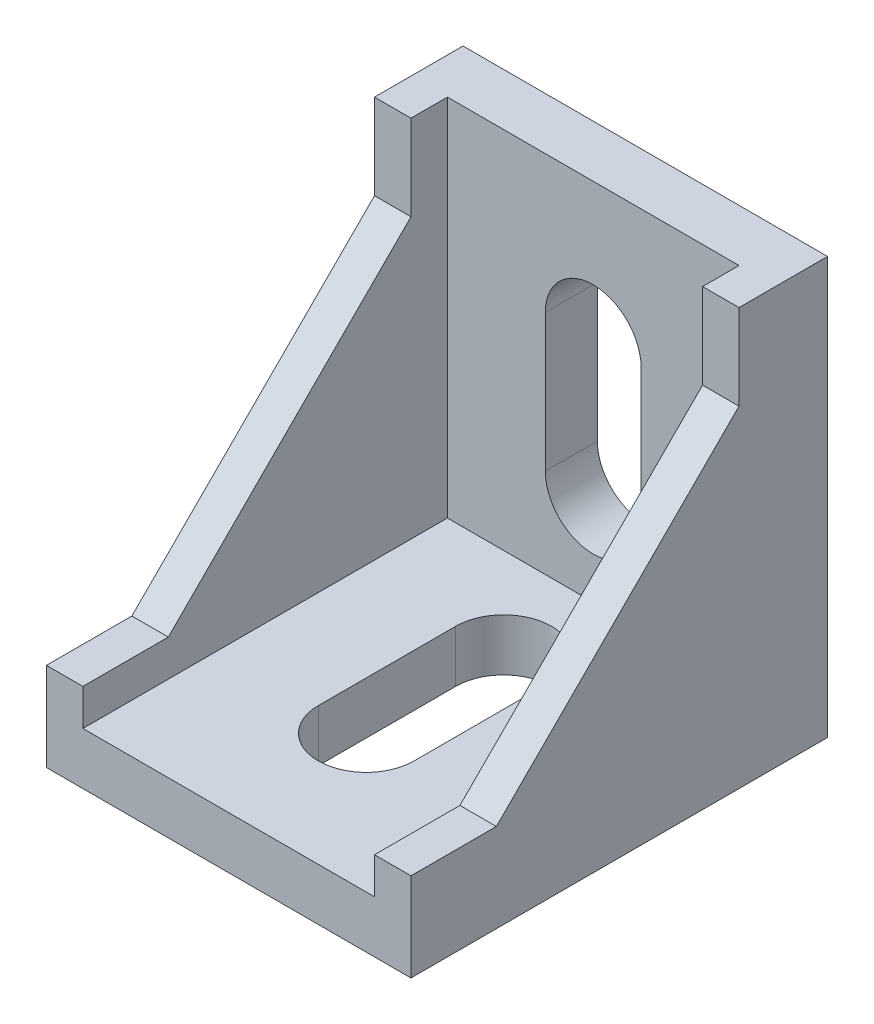
SolidWorks part; units mm, degrees
ref_plane "前视基准面" through (0, 0, 0) normal (0, 0, 1) x (1, 0, 0)
ref_plane "上视基准面" through (0, 0, 0) normal (0, 1, 0) x (1, 0, 0)
ref_plane "右视基准面" through (0, 0, 0) normal (1, 0, 0) x (0, 0, -1)
sketch "草图3" plane through (0, 0, 0) normal (0, 0, 1) x (1, 0, 0)
  line L0 (0, 26.8) -> (0, 13.6) construction
  line L1 (-17.5, 40) -> (17.5, 40)
  line L2 (-17.5, 40) -> (-17.5, 0)
  line L3 (-17.5, 0) -> (17.5, 0)
  line L4 (17.5, 40) -> (17.5, 0)
  line L5 (4.6, 26.8) -> (4.6, 13.6)
  line L6 (-4.6, 26.8) -> (-4.6, 13.6)
  arc A0 (4.6, 26.8) -> (-4.6, 26.8) centre (0, 26.8) ccw
  arc A1 (-4.6, 13.6) -> (4.6, 13.6) centre (0, 13.6) ccw
  point P4 (0, 0)
  point P8 (0, 20.2)
  dimension "D3" = 22.4
  dimension "D4" = 8.6
  dimension "D1" = 35
  dimension "D2" = 40
  dimension "D5" = 9.2
extrude "凸台-拉伸1" add sketch "草图3" along normal blind 5
sketch "草图4" plane through (-17.5, 0, 0) normal (-1, 0, 0) x (0, 0, 1)
  line L0 (5, 40) -> (8.5, 40)
  line L1 (8.5, 40) -> (8.5, 31.8)
  line L2 (8.5, 31.8) -> (31.8, 8.5)
  line L3 (31.8, 8.5) -> (40, 8.5)
  line L4 (40, 8.5) -> (40, 0)
  line L5 (40, 0) -> (5, 0)
  line L6 (5, 0) -> (5, 40)
  line L7 (0, 40) -> (0, 0) construction
  dimension "D1" = 8.5
  dimension "D2" = 8.5
  dimension "D3" = 40
  dimension "D4" = 8.2
extrude "凸台-拉伸2" add sketch "草图4" against normal blind 3.5
mirror "镜向1" about plane through (0, 0, 0) normal (1, 0, 0) of "凸台-拉伸2"
sketch "草图5" plane through (0, 0, 0) normal (0, -1, 0) x (1, 0, 0)
  line L0 (0, 26.8) -> (0, 13.6) construction
  line L1 (-17.5, 0) -> (17.5, 0)
  line L2 (-17.5, 0) -> (-17.5, 40)
  line L3 (-17.5, 40) -> (17.5, 40)
  line L4 (17.5, 0) -> (17.5, 40)
  line L5 (4.6, 26.8) -> (4.6, 13.6)
  line L6 (-4.6, 26.8) -> (-4.6, 13.6)
  arc A0 (4.6, 26.8) -> (-4.6, 26.8) centre (0, 26.8) ccw
  arc A1 (-4.6, 13.6) -> (4.6, 13.6) centre (0, 13.6) ccw
  point P9 (0, 20.2)
  dimension "D2" = 22.4
  dimension "D3" = 8.6
  dimension "D1" = 9.2
extrude "凸台-拉伸3" add sketch "草图5" against normal blind 5
sketch "草图6" plane through (0, 0, 0) normal (1, 0, 0) x (0, 0, -1)
  line L0 (-40, 0) -> (0, 0) construction
  line L1 (-36, 0) -> (-34, 0)
  line L2 (-36, 0) -> (-36, -1.5)
  line L3 (-36, -1.5) -> (-34, -1.5)
  line L4 (-34, 0) -> (-34, -1.5)
  line L5 (-40, 0) -> (-40, 8.5) construction
  line L6 (-20, 0) -> (-20, -10.5773) construction
  line L7 (-6, 0) -> (-6, -1.5)
  line L8 (-4, -1.5) -> (-6, -1.5)
  line L9 (-4, 0) -> (-4, -1.5)
  line L10 (-4, 0) -> (-6, 0)
  line L12 (0, 4) -> (0, 6)
  line L13 (0, 4) -> (1.5, 4)
  line L14 (1.5, 4) -> (1.5, 6)
  line L15 (0, 6) -> (1.5, 6)
  line L16 (0, 34) -> (1.5, 34)
  line L17 (1.5, 36) -> (1.5, 34)
  line L18 (0, 36) -> (1.5, 36)
  line L19 (0, 36) -> (0, 34)
  dimension "D1" = 2
  dimension "D2" = 1.5
  dimension "D3" = 4
extrude "凸台-拉伸4" add sketch "草图6" along normal mid plane 6.2
